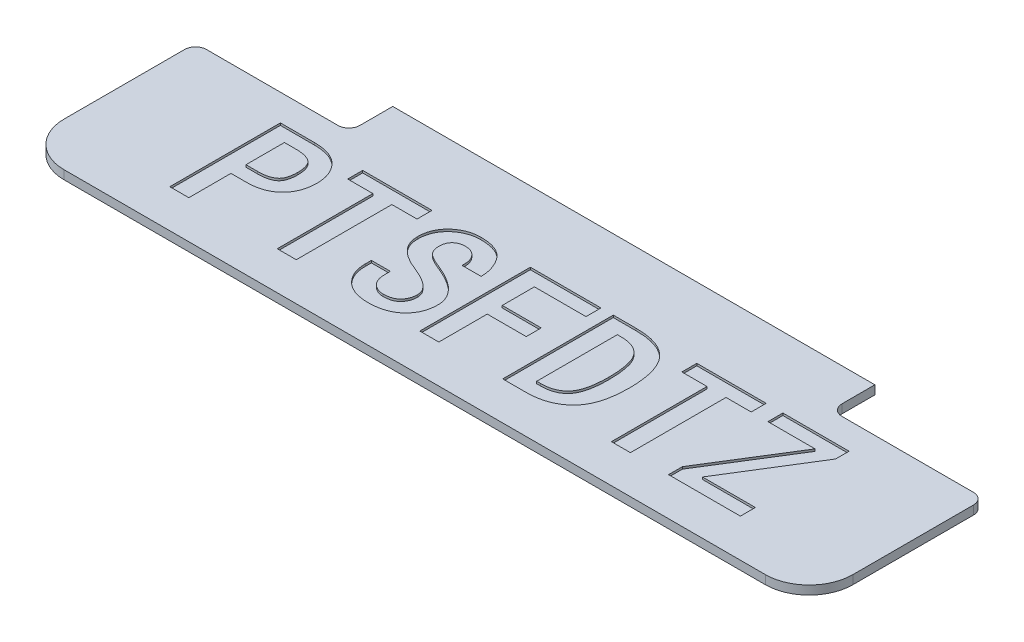
SolidWorks part; units mm, degrees
ref_plane "前视基准面" through (0, 0, 0) normal (0, 0, 1) x (1, 0, 0)
ref_plane "上视基准面" through (0, 0, 0) normal (0, 1, 0) x (1, 0, 0)
ref_plane "右视基准面" through (0, 0, 0) normal (1, 0, 0) x (0, 0, -1)
other "Configuration Table"
sketch "草图1" plane through (0, 0, 0) normal (0, 1, 0) x (1, 0, 0)
  line L1 (-180, -50) -> (180, -50)
  line L2 (-180, -50) -> (-180, 50)
  line L3 (-180, 50) -> (180, 50)
  line L4 (180, -50) -> (180, 50)
  line L5 (-180, -50) -> (180, 50) construction
  line L6 (-180, 50) -> (180, -50) construction
  point P0 (0, 0)
  dimension "D1" = 360
  dimension "D2" = 100
extrude "凸台-拉伸1" add sketch "草图1" along normal blind 4
fillet "圆角3" radius 20 2 edges at (-180, 2, 50) (180, 2, 50)
sketch "草图4" plane through (0, 4, 0) normal (0, 1, 0) x (1, 0, 0)
  line L0 (0, 0) -> (0, 50) construction
  line L1 (-180, 50) -> (-110, 50)
  line L2 (-180, 50) -> (-180, 30)
  line L3 (-180, 30) -> (-110, 30)
  line L4 (-110, 50) -> (-110, 30)
  line L5 (180, 50) -> (-180, 50) construction
  line L6 (180, 30) -> (110, 30)
  line L7 (110, 50) -> (110, 30)
  line L8 (180, 50) -> (110, 50)
  line L9 (180, 50) -> (180, 30)
  dimension "D1" = 70
  dimension "D2" = 20
extrude "切除-拉伸2" cut sketch "草图4" against normal blind 6
fillet "圆角5" radius 5 4 edges at (180, 2, -30) (110, 2, -30) (-110, 2, -30) (-180, 2, -30)
sketch "草图5" plane through (0, 4, 0) normal (0, 1, 0) x (1, 0, 0)
  text T0 "<b>PTSFDTZ</b>" font "黑体" height 50
extrude "切除-拉伸3" cut sketch "草图5" against normal blind 1
